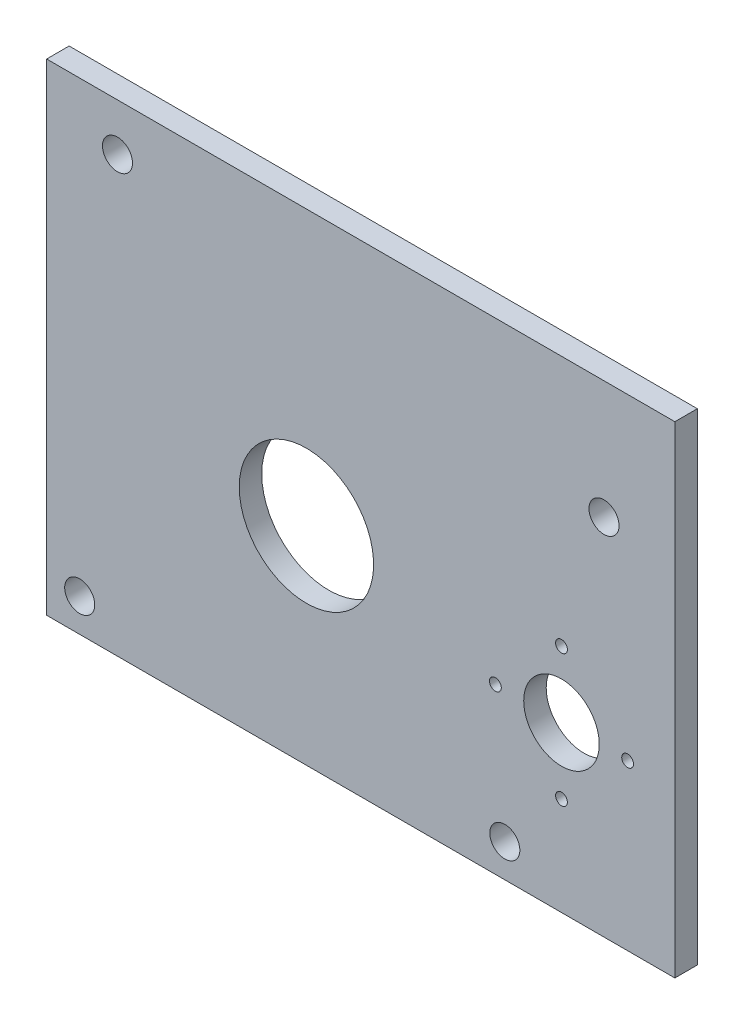
SolidWorks part; units mm, degrees
ref_plane "Front Plane" through (0, 0, 0) normal (0, 0, 1) x (1, 0, 0)
ref_plane "Top Plane" through (0, 0, 0) normal (0, 1, 0) x (1, 0, 0)
ref_plane "Right Plane" through (0, 0, 0) normal (1, 0, 0) x (0, 0, -1)
sketch "Sketch1" plane through (0, 0, 0) normal (0, 0, 1) x (1, 0, 0)
  line L0 (-85.0355, 71.3413) -> (-85.0355, -30.6587)
  line L1 (-85.0355, 71.3413) -> (47.9645, 71.3413)
  line L2 (-85.0355, -30.6587) -> (47.9645, -30.6587)
  line L3 (47.9645, 71.3413) -> (47.9645, -30.6587)
  circle A0 centre (-30.0355, 13.2613) radius 14.225
  circle A2 centre (23.9652, 4.1734) radius 14 construction
  circle A3 centre (23.9652, -9.8266) radius 1.25
  circle A4 centre (37.9652, 4.1734) radius 1.25
  circle A5 centre (23.9652, 18.1734) radius 1.25
  circle A6 centre (9.9652, 4.1734) radius 1.25
  circle A7 centre (23.9652, 4.1734) radius 8
  dimension "D3" = 55
  dimension "D5" = 43.92
  dimension "D4" = 54.0006
  dimension "D1" = 102
  dimension "D2" = 133
extrude "Boss-Extrude2" add sketch "Sketch1" along normal blind 4.7625
sketch "Sketch2" plane through (0, 0, 4.7625) normal (0, 0, 1) x (1, 0, 0)
  line L1 (-85.0355, 71.3413) -> (-85.0355, -30.6587) construction
  line L2 (47.9645, 71.3413) -> (-85.0355, 71.3413) construction
  line L3 (47.9645, -30.6587) -> (47.9645, 71.3413) construction
  line L4 (-85.0355, -30.6587) -> (47.9645, -30.6587) construction
  circle A1 centre (-70.0355, 61.3413) radius 3.18
  circle A2 centre (32.9645, 46.3413) radius 3.18
  circle A3 centre (11.9645, -23.6587) radius 3.18
  circle A4 centre (-78.0355, -23.6587) radius 3.18
  dimension "D1" = 15
  dimension "D3" = 15
  dimension "D5" = 7
  dimension "D7" = 7
  dimension "D2" = 10
  dimension "D4" = 25
  dimension "D6" = 36
extrude "Cut-Extrude1" cut sketch "Sketch2" against normal up to next
